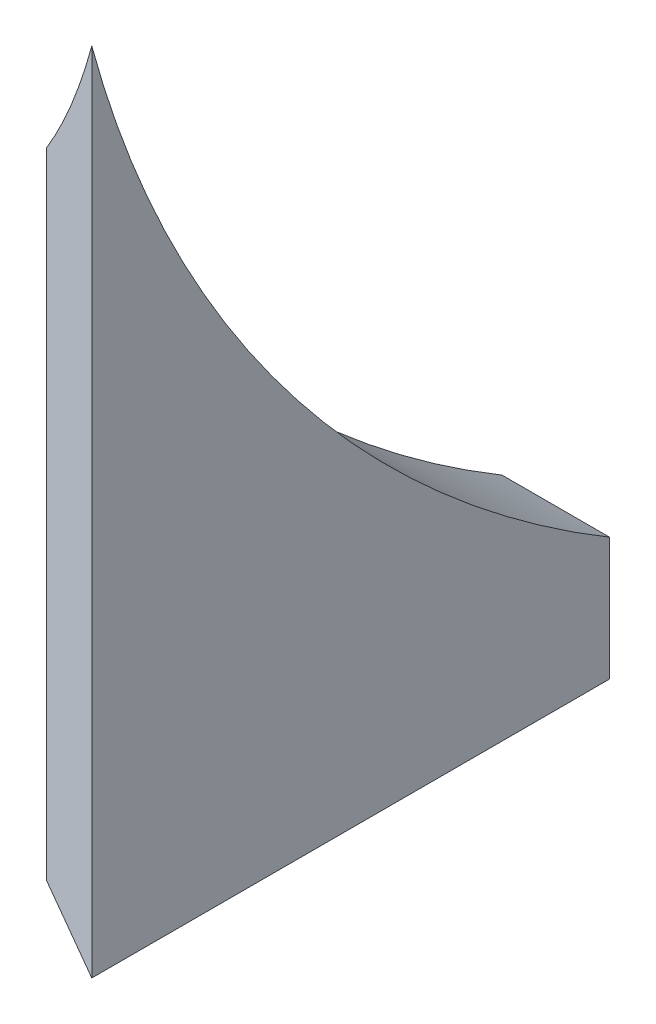
SolidWorks part; units mm, degrees
ref_plane "Front Plane" through (0, 0, 0) normal (0, 0, 1) x (1, 0, 0)
ref_plane "Top Plane" through (0, 0, 0) normal (0, 1, 0) x (1, 0, 0)
ref_plane "Right Plane" through (0, 0, 0) normal (1, 0, 0) x (0, 0, -1)
sketch "Sketch1" plane through (0, 0, 0) normal (1, 0, 0) x (0, 0, -1)
  line L0 (-11.8671, 22.332) -> (-11.8671, -7.668)
  line L1 (-11.8671, -7.668) -> (18.1329, -7.668)
  arc A0 (-11.8671, 22.332) -> (18.1329, -7.668) centre (29.2351, 33.4343) ccw
  dimension "D1" = 30
  dimension "D2" = 30
extrude "Boss-Extrude1" add sketch "Sketch1" along normal blind 4
sketch "Sketch2" plane through (4, 0, 0) normal (1, 0, 0) x (0, 0, -1)
  line L0 (-11.8671, 22.332) -> (-11.8671, -7.668) construction
  line L1 (18.1329, -7.668) -> (7.3829, -7.668)
  line L2 (18.1329, -7.668) -> (18.1329, 12.6592)
  line L3 (18.1329, 12.6592) -> (7.3829, 12.6592)
  line L4 (7.3829, -7.668) -> (7.3829, 12.6592)
  dimension "D1" = 19.25
extrude "Cut-Extrude1" cut sketch "Sketch2" against normal blind 4
sketch "Sketch4" plane through (0, -7.668, 0) normal (0, -1, 0) x (1, 0, 0)
  line L0 (0, 11.8671) -> (0, 9.5577)
  line L1 (0, 11.8671) -> (0, -7.3829) construction
  line L2 (0, 9.5577) -> (4, 11.8671)
  line L3 (4, 11.8671) -> (0, 11.8671)
  dimension "D1" = 30
extrude "Cut-Extrude2" cut sketch "Sketch4" against normal blind 50.8
